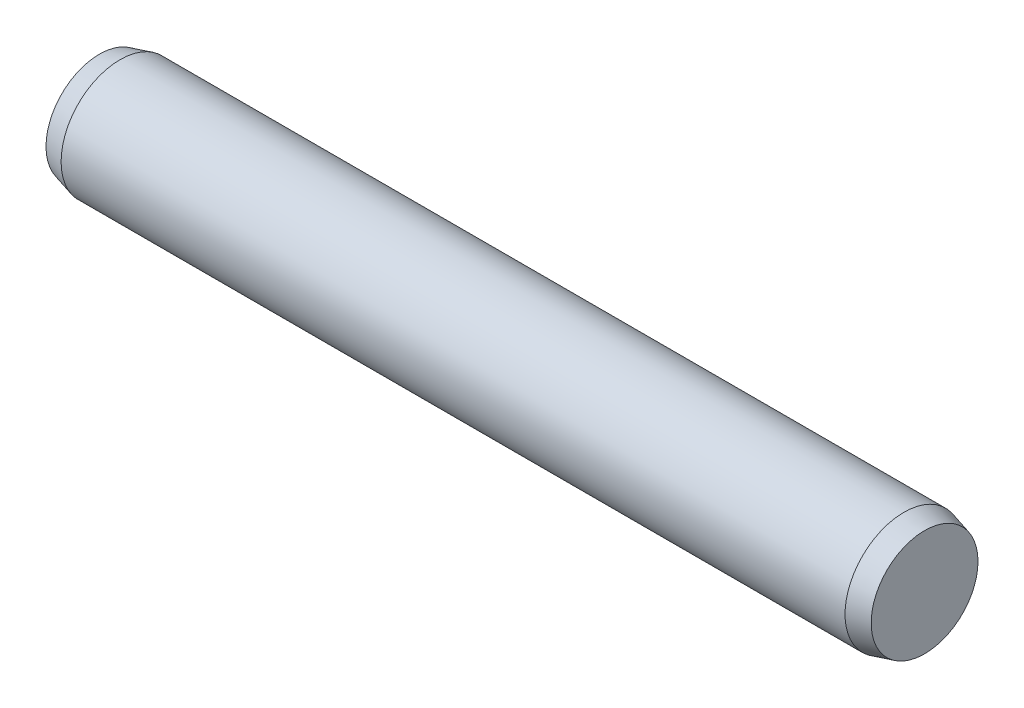
SolidWorks part; units mm, degrees
ref_plane "Front Plane" through (0, 0, 0) normal (0, 0, 1) x (1, 0, 0)
ref_plane "Top Plane" through (0, 0, 0) normal (0, 1, 0) x (1, 0, 0)
ref_plane "Right Plane" through (0, 0, 0) normal (1, 0, 0) x (0, 0, -1)
sketch "Sketch1" plane through (0, 0, 0) normal (0, 0, 1) x (1, 0, 0)
  line L0 (-6.65, 0) -> (6.65, 0) construction
  line L1 (6.65, 1) -> (6.65, -1) construction
  line L2 (-6.65, 1) -> (-6.65, -1) construction
  line L3 (7, 1) -> (7, -1) construction
  line L4 (-7, 1) -> (-7, -1) construction
  line L5 (-6.65, 0) -> (-7, 0) construction
  line L6 (6.65, 0) -> (7, 0) construction
  dimension "D1" = 0.35
  dimension "Dia" = 2
  dimension "Length" = 14
  dimension "C" = 0.35
sketch "Sketch2" plane through (0, 0, 0) normal (1, 0, 0) x (0, 0, -1)
  circle A0 centre (0, 0) radius 1
extrude "Extrude1" add sketch "Sketch2" against normal up to vertex (6.65 mm away) and the other way up to vertex (6.65 mm away) up to point (-6.65, 1, 0) other way up to point (6.65, 1, 0)
sketch "Sketch3" plane through (6.65, 0, 0) normal (1, 0, 0) x (0, 0, -1)
  circle A1 centre (0, 0) radius 1
  circle A2 centre (0, 0) radius 1
  dimension "D1" = 0
extrude "Extrude2" add sketch "Sketch3" along normal up to vertex (0.35 mm away) draft 15 up to point (7, 0, 0)
sketch "Sketch4" plane through (-6.65, 0, 0) normal (-1, 0, 0) x (0, 0, 1)
  circle A1 centre (0, 0) radius 1
  circle A2 centre (0, 0) radius 1
  dimension "D1" = 0
extrude "Extrude3" add sketch "Sketch4" along normal up to vertex (0.35 mm away) draft 15 up to point (-7, 0, 0)
equation "\"D1@Sketch1\" = \"C@Sketch1\""
